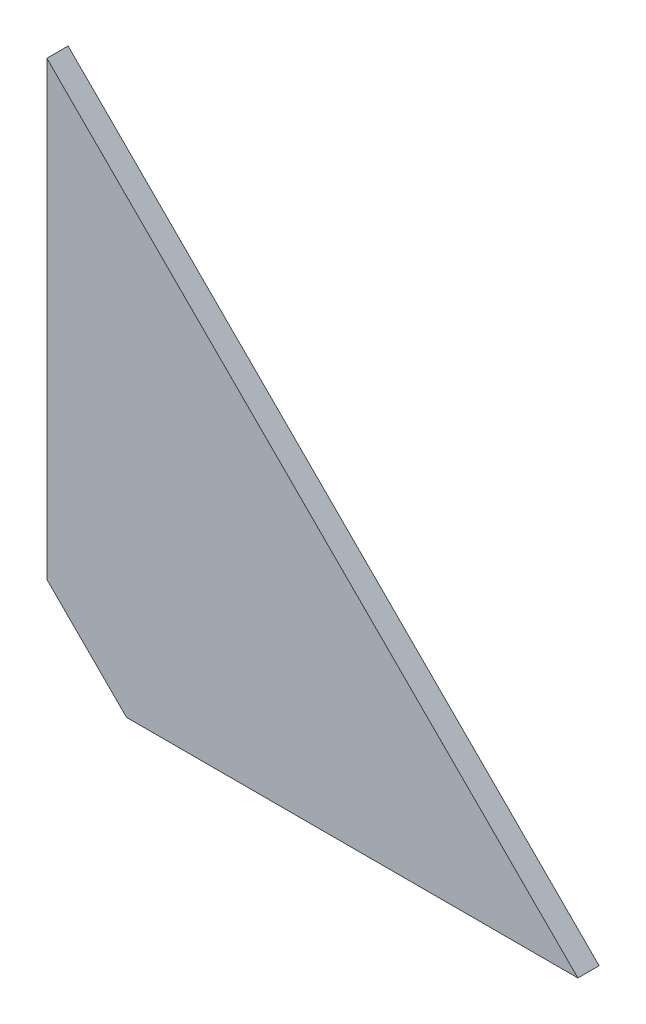
SolidWorks part; units mm, degrees
material "PW80:Mi:0:41:Ar:0:-1:C1:1:2:3:Re:15:"
ref_plane "Plan1" through (0, 0, 0) normal (0, 0, 1) x (1, 0, 0)
ref_plane "Plan2" through (0, 0, 0) normal (0, 1, 0) x (1, 0, 0)
ref_plane "Plan3" through (0, 0, 0) normal (1, 0, 0) x (0, 0, -1)
sketch "Esquisse1" plane through (0, 0, 0) normal (0, 0, 1) x (1, 0, 0)
  line L0 (0, 200) -> (200, 0)
  line L1 (30, 0) -> (200, 0)
  line L2 (0, 30) -> (0, 200)
  line L5 (30, 0) -> (0, 30)
extrude "Base-Extrusion" add sketch "Esquisse1" along normal blind 8
